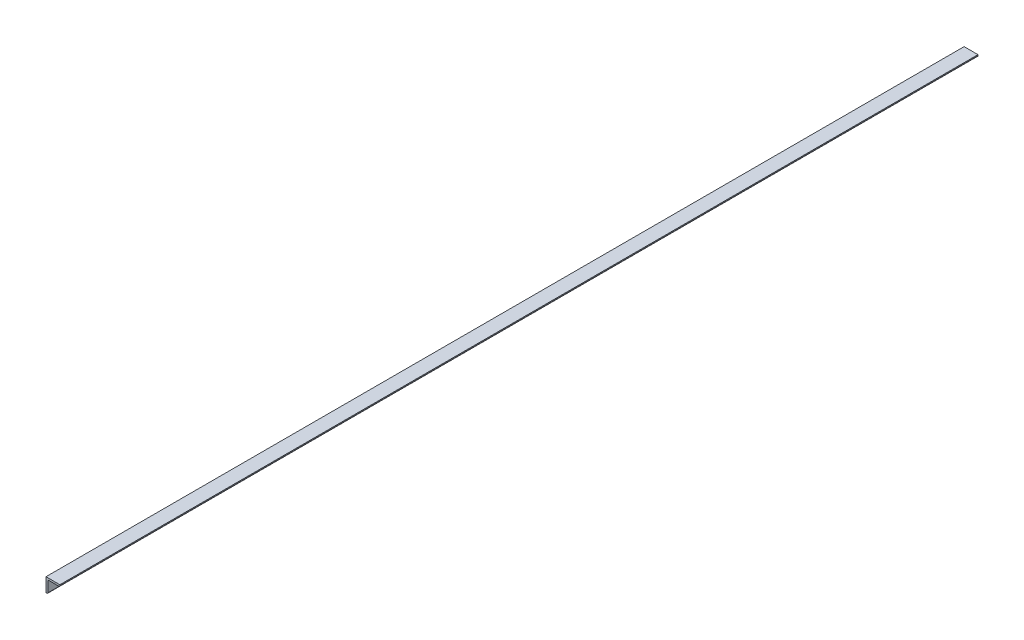
SolidWorks part; units mm, degrees
material "ASTM A36 Steel"
ref_plane "Front Plane" through (0, 0, 0) normal (0, 0, 1) x (1, 0, 0)
ref_plane "Top Plane" through (0, 0, 0) normal (0, 1, 0) x (1, 0, 0)
ref_plane "Right Plane" through (0, 0, 0) normal (1, 0, 0) x (0, 0, -1)
sketch "Sketch1" plane through (0, 0, 0) normal (0, 0, 1) x (1, 0, 0)
  line L0 (-8.625, 38.8125) -> (-38.625, 38.8125)
  line L1 (-38.625, 38.8125) -> (-38.625, 8.8125)
  line L2 (-38.625, 8.8125) -> (-36.625, 8.8125)
  line L3 (-34.625, 10.8125) -> (-34.625, 32.8125)
  line L4 (-32.625, 34.8125) -> (-10.625, 34.8125)
  line L5 (-8.625, 36.8125) -> (-8.625, 38.8125)
  arc A0 (-36.625, 8.8125) -> (-34.625, 10.8125) centre (-36.625, 10.8125) ccw
  arc A1 (-10.625, 34.8125) -> (-8.625, 36.8125) centre (-10.625, 36.8125) ccw
  arc A2 (-34.625, 32.8125) -> (-32.625, 34.8125) centre (-32.625, 32.8125) cw
  point P8 (-34.625, 8.8125)
  point P11 (-8.625, 34.8125)
  dimension "D5" = 2
  dimension "D1" = 30
  dimension "D2" = 30
  dimension "D3" = 4
  dimension "D4" = 4
extrude "Boss-Extrude1" add sketch "Sketch1" along normal blind 1985
